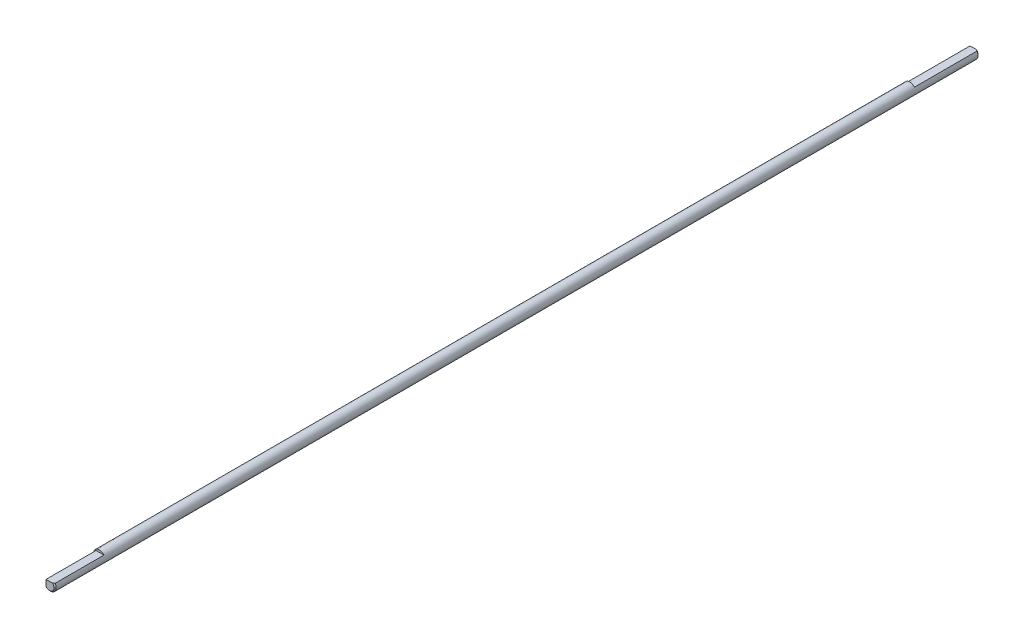
SolidWorks part; units mm, degrees
material "AISI 1020"
ref_plane "Спереди" through (0, 0, 0) normal (0, 0, 1) x (1, 0, 0)
ref_plane "Сверху" through (0, 0, 0) normal (0, 1, 0) x (1, 0, 0)
ref_plane "Справа" through (0, 0, 0) normal (1, 0, 0) x (0, 0, -1)
sketch "Эскиз1" plane through (0, 0, 0) normal (0, 0, 1) x (1, 0, 0)
  circle A0 centre (0, 0) radius 2.5
  dimension "D1" = 5
extrude "Body" add sketch "Эскиз1" along normal blind 406.5
chamfer "ChamferEdges" distance 0.5 angle 45 2 edges at (2.5, 0, 406.5) (2.5, 0, 0)
sketch "Sketch2" plane through (0, 0, 0) normal (1, 0, 0) x (0, 0, -1)
  line L0 (-406.5, 2) -> (-406.5, -2) construction
  line L1 (-28, 4.0099) -> (0.6305, 4.0099)
  line L2 (-28, 4.0099) -> (-28, 1.5)
  line L3 (-28, 1.5) -> (0.6305, 1.5)
  line L4 (0.6305, 4.0099) -> (0.6305, 1.5)
  line L6 (-406, -2.5) -> (-0.5, -2.5) construction
  line L11 (-384.5, 3.4421) -> (-384.5, 1.5)
  line L13 (-412.5, 3.4421) -> (-384.5, 3.4421)
  line L14 (-412.5, 3.4421) -> (-412.5, 1.5)
  line L15 (-412.5, 1.5) -> (-384.5, 1.5)
  dimension "D1" = 28
  dimension "D2" = 4
  dimension "D4" = 22
extrude "FirstSlots" cut sketch "Sketch2" against normal through all both and the other way through all
pattern_circular "CirPattern1" count 2 every 90 about axis through (0, 0, 406.5) along (0, 0, 1) of "FirstSlots"
